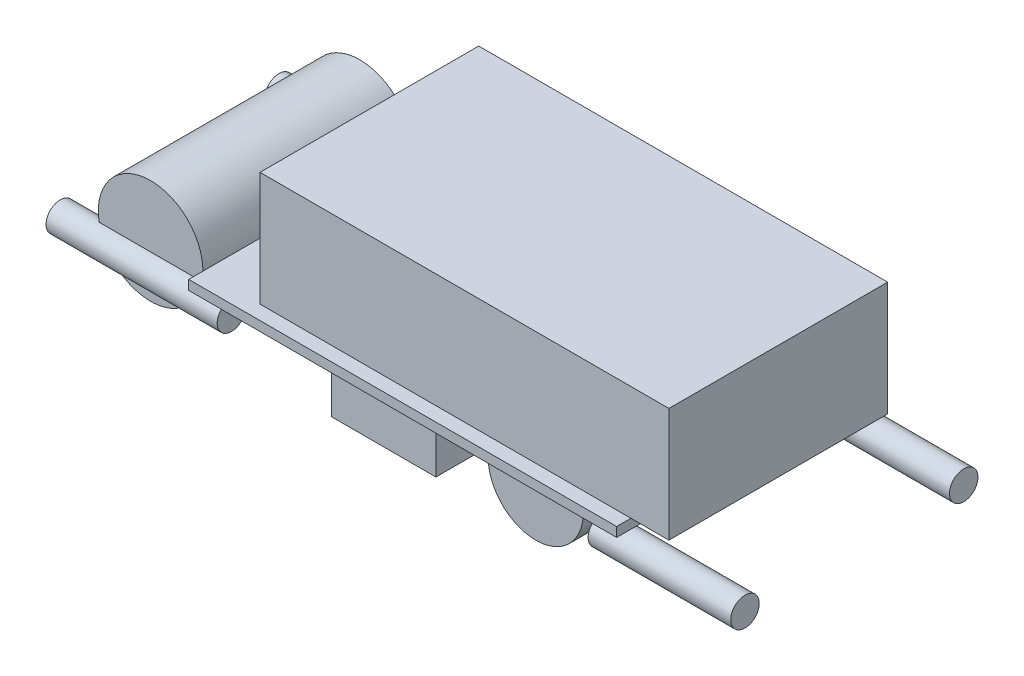
SolidWorks part; units mm, degrees
ref_plane "Alzado" through (0, 0, 0) normal (0, 0, 1) x (1, 0, 0)
ref_plane "Planta" through (0, 0, 0) normal (0, 1, 0) x (1, 0, 0)
ref_plane "Vista lateral" through (0, 0, 0) normal (1, 0, 0) x (0, 0, -1)
sketch "Croquis1" plane through (0, 0, 0) normal (0, 1, 0) x (1, 0, 0)
  line L1 (0, 0) -> (43, 0)
  line L2 (0, 0) -> (0, 23)
  line L3 (0, 23) -> (43, 23)
  line L4 (43, 0) -> (43, 23)
  dimension "D1" = 23
  dimension "D2" = 43
extrude "Saliente-Extruir1" add sketch "Croquis1" along normal blind 12
sketch "Croquis2" plane through (0, 0, 0) normal (0, -1, 0) x (1, 0, 0)
  line L0 (0, -23) -> (0, 0) construction
  line L1 (-6, 1.5) -> (39, 1.5)
  line L2 (-6, 1.5) -> (-6, -24.5)
  line L3 (-6, -24.5) -> (39, -24.5)
  line L4 (39, 1.5) -> (39, -24.5)
  line L5 (43, 0) -> (43, -23) construction
  line L6 (0, 0) -> (43, 0) construction
  line L7 (43, -23) -> (0, -23) construction
  dimension "D1" = 6
  dimension "D2" = 4
  dimension "D3" = 1.5
  dimension "D4" = 1.5
extrude "Saliente-Extruir2" add sketch "Croquis2" along normal blind 1
sketch "Croquis4" plane through (0, 0, 0) normal (0, 0, 1) x (1, 0, 0)
  line L0 (39, 0) -> (-6, 0) construction
  circle A0 centre (-11.5, 0) radius 5.5
  point P7 (-10.7971, 3.4755)
  dimension "D2" = 11
  dimension "D1" = 5.5
extrude "Saliente-Extruir3" add sketch "Croquis4" against normal blind 22 separate body
sketch "Croquis6" plane through (0, -1, 0) normal (0, -1, 0) x (1, 0, 0)
  line L0 (-6, 1.5) -> (-6, -24.5) construction
  line L1 (8, 0.5) -> (19, 0.5)
  line L2 (5, -11.5) -> (5, -23.5)
  line L3 (5, -23.5) -> (19, -23.5)
  line L4 (19, 0.5) -> (19, -23.5)
  line L5 (5, -11.5) -> (19, -11.5) construction
  line L6 (-6, -11.5) -> (39, -11.5) construction
  line L7 (39, -24.5) -> (39, 1.5) construction
  line L8 (8, 0.5) -> (8, -11.5)
  line L9 (8, -11.5) -> (5, -11.5)
  dimension "D1" = 24
  dimension "D2" = 14
  dimension "D3" = 11
  dimension "D4" = 3
extrude "Saliente-Extruir4" add sketch "Croquis6" along normal blind 5
sketch "Croquis7" plane through (0, 0, -23) normal (0, 0, -1) x (-1, 0, 0)
  line L0 (-39, -1) -> (6, -1) construction
  circle A0 centre (-25, -6) radius 5
  dimension "D2" = 10
  dimension "D1" = 5
  dimension "D3" = 6
extrude "Saliente-Extruir5" add sketch "Croquis7" against normal blind 13 from offset 6 separate body offset against normal yes
sketch "Croquis8" plane through (39, 0, 0) normal (1, 0, 0) x (0, 0, -1)
  line L0 (4, -1) -> (4, -11) construction
  line L1 (17, -11) -> (17, -1) construction
  line L3 (23.5, -1) -> (-0.5, -1) construction
  line L4 (24.5, -1) -> (-1.5, -1) construction
  circle A0 centre (0, -2.5) radius 1.5
  circle A1 centre (23, -2.5) radius 1.5
  point P10 (26.445, -4.0859)
  dimension "D1" = 3
  dimension "D2" = 3
  dimension "D4" = 6
  dimension "D5" = 1.5
  dimension "D3" = 4
  dimension "D6" = 1.5
extrude "Saliente-Extruir6" add sketch "Croquis8" along normal blind 12 and the other way blind 3 separate body
sketch "Croquis9" plane through (-6, 0, 0) normal (-1, 0, 0) x (0, 0, 1)
  circle A0 centre (-23, -2.5) radius 1.5
  circle A1 centre (0, -2.5) radius 1.5
extrude "Saliente-Extruir7" add sketch "Croquis9" against normal blind 3 and the other way blind 15
